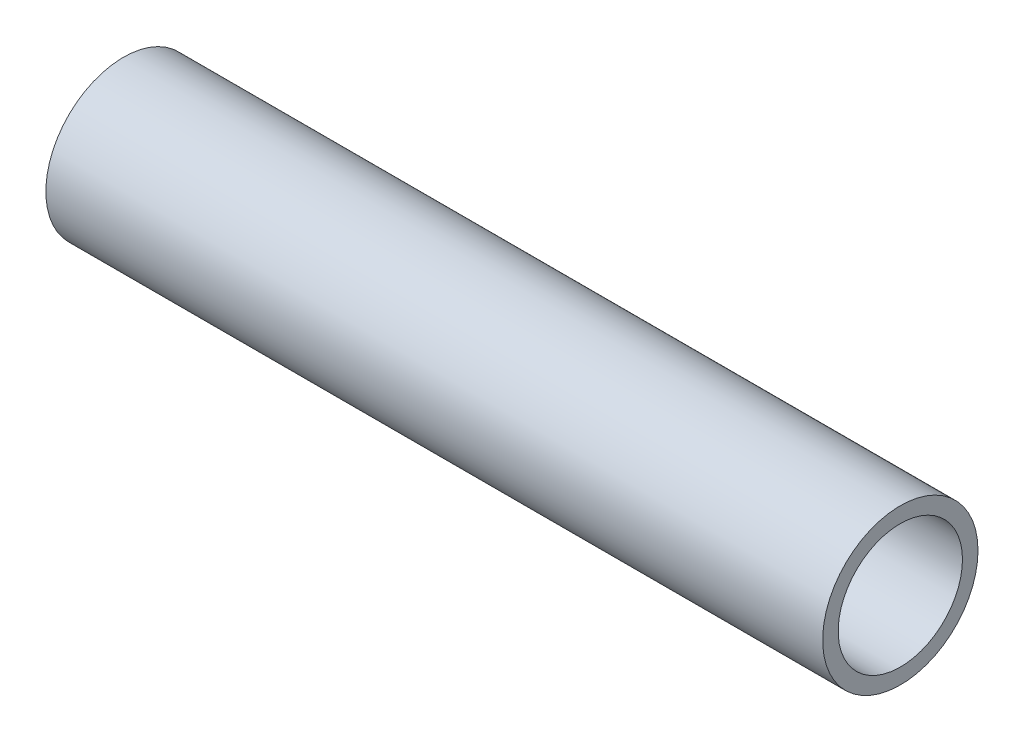
SolidWorks part; units mm, degrees
material "PET"
ref_plane "Front Plane" through (0, 0, 0) normal (0, 0, 1) x (1, 0, 0)
ref_plane "Top Plane" through (0, 0, 0) normal (0, 1, 0) x (1, 0, 0)
ref_plane "Right Plane" through (0, 0, 0) normal (1, 0, 0) x (0, 0, -1)
sketch "Sketch1" plane through (0, 0, 0) normal (1, 0, 0) x (0, 0, -1)
  circle A0 centre (0, 0) radius 5
  circle A1 centre (0, 0) radius 4
  dimension "D1" = 10
  dimension "D2" = 8
extrude "Boss-Extrude2" add sketch "Sketch1" along normal mid plane 50
